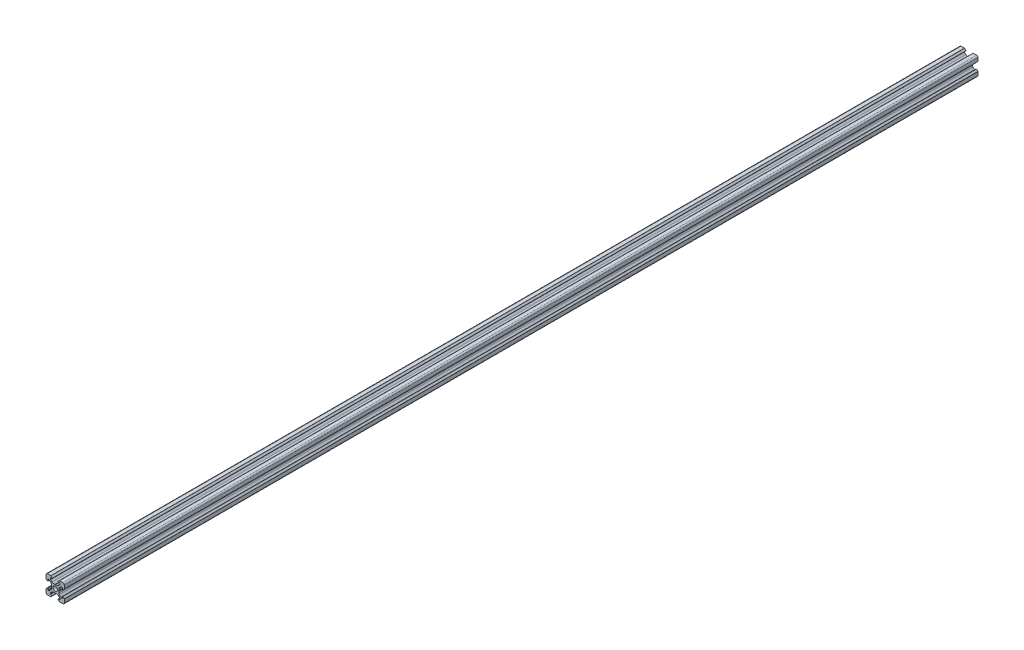
SolidWorks part; units mm, degrees
material "6061 Сплав"
ref_plane "Спереди" through (0, 0, 0) normal (0, 0, 1) x (1, 0, 0)
ref_plane "Сверху" through (0, 0, 0) normal (0, 1, 0) x (1, 0, 0)
ref_plane "Справа" through (0, 0, 0) normal (1, 0, 0) x (0, 0, -1)
sketch "Сечение" plane through (0, 0, 0) normal (0, 0, 1) x (1, 0, 0)
  line L0 (-4, 1.8988) -> (-4, 0.3377)
  line L1 (-3.9452, 0.1815) -> (-3.8, 0)
  line L2 (-3.8, 0) -> (-3.9452, -0.1815)
  line L3 (-4, -0.3377) -> (-4, -1.8988)
  line L4 (-4.5858, -3.313) -> (-6.2799, -5.0071)
  line L5 (-6.987, -5.3) -> (-7.8, -5.3)
  line L6 (-8, -5.1) -> (-8, -3.33)
  line L7 (-8.4268, -3.1532) -> (-9.9268, -4.6532)
  line L8 (-10, -4.83) -> (-10, -8.5)
  line L9 (-8.5, -10) -> (-4.83, -10)
  line L10 (-4.6532, -9.9268) -> (-3.1532, -8.4268)
  line L11 (-3.33, -8) -> (-5.1, -8)
  line L12 (-5.3, -7.8) -> (-5.3, -6.987)
  line L13 (-5.0071, -6.2799) -> (-3.313, -4.5858)
  line L14 (-1.8988, -4) -> (-0.3377, -4)
  line L15 (-0.1815, -3.9452) -> (0, -3.8)
  line L16 (0, -3.8) -> (0.1815, -3.9452)
  line L17 (0.3377, -4) -> (1.8988, -4)
  line L18 (3.313, -4.5858) -> (5.0071, -6.2799)
  line L19 (5.3, -6.987) -> (5.3, -7.8)
  line L20 (5.1, -8) -> (3.33, -8)
  line L21 (3.1532, -8.4268) -> (4.6532, -9.9268)
  line L22 (4.83, -10) -> (8.5, -10)
  line L23 (10, -8.5) -> (10, -4.83)
  line L24 (9.9268, -4.6532) -> (8.4268, -3.1532)
  line L25 (8, -3.33) -> (8, -5.1)
  line L26 (7.8, -5.3) -> (6.987, -5.3)
  line L27 (6.2799, -5.0071) -> (4.5858, -3.313)
  line L28 (4, -1.8988) -> (4, -0.3377)
  line L29 (3.9452, -0.1815) -> (3.8, 0)
  line L30 (3.8, 0) -> (3.9452, 0.1815)
  line L31 (4, 0.3377) -> (4, 1.8988)
  line L32 (4.5858, 3.313) -> (6.2799, 5.0071)
  line L33 (6.987, 5.3) -> (7.8, 5.3)
  line L34 (8, 5.1) -> (8, 3.33)
  line L35 (8.4268, 3.1532) -> (9.9268, 4.6532)
  line L36 (10, 4.83) -> (10, 8.5)
  line L37 (8.5, 10) -> (4.83, 10)
  line L38 (4.6532, 9.9268) -> (3.1532, 8.4268)
  line L39 (3.33, 8) -> (5.1, 8)
  line L40 (5.3, 7.8) -> (5.3, 6.987)
  line L41 (5.0071, 6.2799) -> (3.313, 4.5858)
  line L42 (1.8988, 4) -> (0.3377, 4)
  line L43 (0.1815, 3.9452) -> (0, 3.8)
  line L44 (0, 3.8) -> (-0.1815, 3.9452)
  line L45 (-0.3377, 4) -> (-1.8988, 4)
  line L46 (-3.313, 4.5858) -> (-5.0071, 6.2799)
  line L47 (-5.3, 6.987) -> (-5.3, 7.8)
  line L48 (-5.1, 8) -> (-3.33, 8)
  line L49 (-3.1532, 8.4268) -> (-4.6532, 9.9268)
  line L50 (-4.83, 10) -> (-8.5, 10)
  line L51 (-10, 8.5) -> (-10, 4.83)
  line L52 (-9.9268, 4.6532) -> (-8.4268, 3.1532)
  line L53 (-8, 3.33) -> (-8, 5.1)
  line L54 (-7.8, 5.3) -> (-6.987, 5.3)
  line L55 (-6.2799, 5.0071) -> (-4.5858, 3.313)
  circle A0 centre (0, 0) radius 2.5
  arc A1 (-4, 0.3377) -> (-3.9452, 0.1815) centre (-3.75, 0.3377) ccw
  arc A2 (-3.9452, -0.1815) -> (-4, -0.3377) centre (-3.75, -0.3377) ccw
  arc A3 (-4, -1.8988) -> (-4.5858, -3.313) centre (-6, -1.8988) cw
  arc A4 (-6.2799, -5.0071) -> (-6.987, -5.3) centre (-6.987, -4.3) cw
  arc A5 (-7.8, -5.3) -> (-8, -5.1) centre (-7.8, -5.1) cw
  arc A6 (-8, -3.33) -> (-8.4268, -3.1532) centre (-8.25, -3.33) ccw
  arc A7 (-9.9268, -4.6532) -> (-10, -4.83) centre (-9.75, -4.83) ccw
  arc A8 (-10, -8.5) -> (-8.5, -10) centre (-8.5, -8.5) ccw
  arc A9 (-4.83, -10) -> (-4.6532, -9.9268) centre (-4.83, -9.75) ccw
  arc A10 (-3.1532, -8.4268) -> (-3.33, -8) centre (-3.33, -8.25) ccw
  arc A11 (-5.1, -8) -> (-5.3, -7.8) centre (-5.1, -7.8) cw
  arc A12 (-5.3, -6.987) -> (-5.0071, -6.2799) centre (-4.3, -6.987) cw
  arc A13 (-3.313, -4.5858) -> (-1.8988, -4) centre (-1.8988, -6) cw
  arc A14 (-0.3377, -4) -> (-0.1815, -3.9452) centre (-0.3377, -3.75) ccw
  arc A15 (0.1815, -3.9452) -> (0.3377, -4) centre (0.3377, -3.75) ccw
  arc A16 (1.8988, -4) -> (3.313, -4.5858) centre (1.8988, -6) cw
  arc A17 (5.0071, -6.2799) -> (5.3, -6.987) centre (4.3, -6.987) cw
  arc A18 (5.3, -7.8) -> (5.1, -8) centre (5.1, -7.8) cw
  arc A19 (3.33, -8) -> (3.1532, -8.4268) centre (3.33, -8.25) ccw
  arc A20 (4.6532, -9.9268) -> (4.83, -10) centre (4.83, -9.75) ccw
  arc A21 (8.5, -10) -> (10, -8.5) centre (8.5, -8.5) ccw
  arc A22 (10, -4.83) -> (9.9268, -4.6532) centre (9.75, -4.83) ccw
  arc A23 (8.4268, -3.1532) -> (8, -3.33) centre (8.25, -3.33) ccw
  arc A24 (8, -5.1) -> (7.8, -5.3) centre (7.8, -5.1) cw
  arc A25 (6.987, -5.3) -> (6.2799, -5.0071) centre (6.987, -4.3) cw
  arc A26 (4.5858, -3.313) -> (4, -1.8988) centre (6, -1.8988) cw
  arc A27 (4, -0.3377) -> (3.9452, -0.1815) centre (3.75, -0.3377) ccw
  arc A28 (3.9452, 0.1815) -> (4, 0.3377) centre (3.75, 0.3377) ccw
  arc A29 (4, 1.8988) -> (4.5858, 3.313) centre (6, 1.8988) cw
  arc A30 (6.2799, 5.0071) -> (6.987, 5.3) centre (6.987, 4.3) cw
  arc A31 (7.8, 5.3) -> (8, 5.1) centre (7.8, 5.1) cw
  arc A32 (8, 3.33) -> (8.4268, 3.1532) centre (8.25, 3.33) ccw
  arc A33 (9.9268, 4.6532) -> (10, 4.83) centre (9.75, 4.83) ccw
  arc A34 (10, 8.5) -> (8.5, 10) centre (8.5, 8.5) ccw
  arc A35 (4.83, 10) -> (4.6532, 9.9268) centre (4.83, 9.75) ccw
  arc A36 (3.1532, 8.4268) -> (3.33, 8) centre (3.33, 8.25) ccw
  arc A37 (5.1, 8) -> (5.3, 7.8) centre (5.1, 7.8) cw
  arc A38 (5.3, 6.987) -> (5.0071, 6.2799) centre (4.3, 6.987) cw
  arc A39 (3.313, 4.5858) -> (1.8988, 4) centre (1.8988, 6) cw
  arc A40 (0.3377, 4) -> (0.1815, 3.9452) centre (0.3377, 3.75) ccw
  arc A41 (-0.1815, 3.9452) -> (-0.3377, 4) centre (-0.3377, 3.75) ccw
  arc A42 (-1.8988, 4) -> (-3.313, 4.5858) centre (-1.8988, 6) cw
  arc A43 (-5.0071, 6.2799) -> (-5.3, 6.987) centre (-4.3, 6.987) cw
  arc A44 (-5.3, 7.8) -> (-5.1, 8) centre (-5.1, 7.8) cw
  arc A45 (-3.33, 8) -> (-3.1532, 8.4268) centre (-3.33, 8.25) ccw
  arc A46 (-4.6532, 9.9268) -> (-4.83, 10) centre (-4.83, 9.75) ccw
  arc A47 (-8.5, 10) -> (-10, 8.5) centre (-8.5, 8.5) ccw
  arc A48 (-10, 4.83) -> (-9.9268, 4.6532) centre (-9.75, 4.83) ccw
  arc A49 (-8.4268, 3.1532) -> (-8, 3.33) centre (-8.25, 3.33) ccw
  arc A50 (-8, 5.1) -> (-7.8, 5.3) centre (-7.8, 5.1) cw
  arc A51 (-6.987, 5.3) -> (-6.2799, 5.0071) centre (-6.987, 4.3) cw
  arc A52 (-4.5858, 3.313) -> (-4, 1.8988) centre (-6, 1.8988) cw
extrude "Длина" add sketch "Сечение" against normal blind 1000
